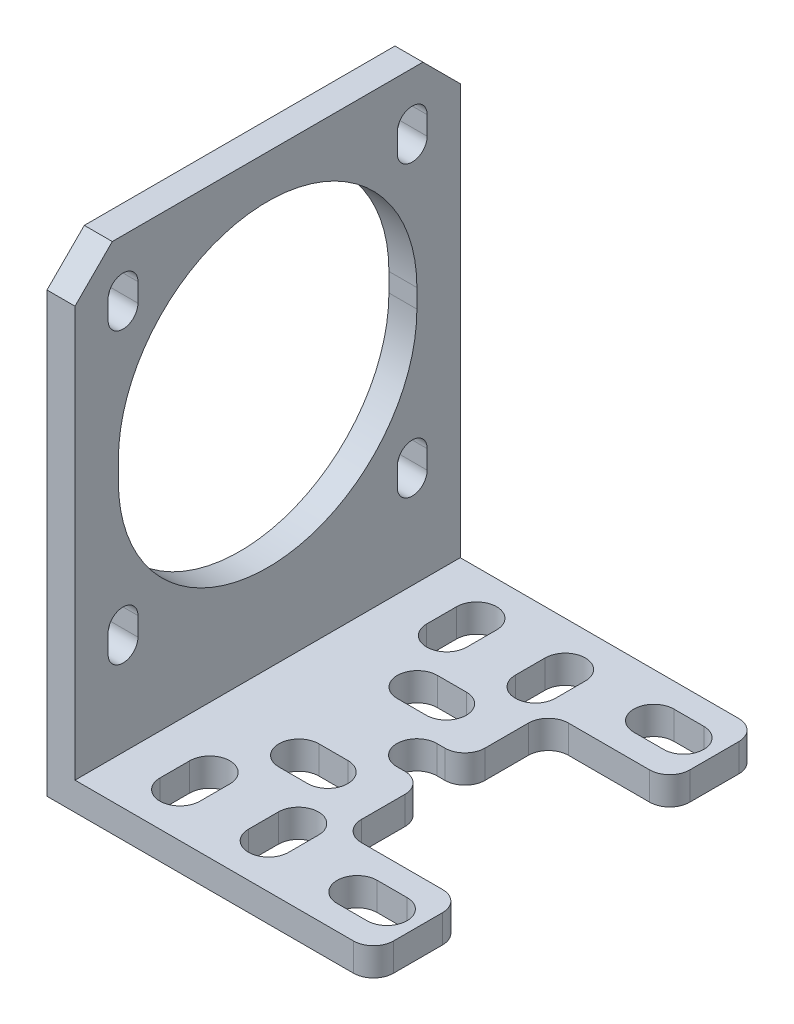
SolidWorks part; units mm, degrees
material "1060 Alloy"
ref_plane "Front Plane" through (0, 0, 0) normal (0, 0, 1) x (1, 0, 0)
ref_plane "Top Plane" through (0, 0, 0) normal (0, 1, 0) x (1, 0, 0)
ref_plane "Right Plane" through (0, 0, 0) normal (1, 0, 0) x (0, 0, -1)
sketch "Sketch1" plane through (0, 0, 0) normal (0, 1, 0) x (1, 0, 0)
  line L0 (-22.0687, 0) -> (25.1163, 0) construction
  line L1 (-17.5, 20.65) -> (15.35, 20.65)
  line L2 (-17.5, 20.65) -> (-17.5, -20.65)
  line L3 (-17.5, -20.65) -> (15.35, -20.65)
  line L4 (17.5, 18.5) -> (17.5, 13.25)
  line L5 (-17.5, 20.65) -> (17.5, -20.65) construction
  line L6 (-17.5, -20.65) -> (17.5, 20.65) construction
  line L7 (-8, 15.9) -> (-8, 12.7) construction
  line L8 (-5.85, 15.9) -> (-5.85, 12.7)
  line L9 (-10.15, 15.9) -> (-10.15, 12.7)
  line L10 (1.5, 15.9) -> (1.5, 12.7) construction
  line L11 (3.65, 15.9) -> (3.65, 12.7)
  line L12 (-0.65, 15.9) -> (-0.65, 12.7)
  line L13 (11, 15.9) -> (14.2, 15.9) construction
  line L14 (11, 18.05) -> (14.2, 18.05)
  line L15 (11, 13.75) -> (14.2, 13.75)
  line L16 (-4.8, 6.35) -> (-1.7, 6.35) construction
  line L17 (-4.8, 8.5) -> (-1.7, 8.5)
  line L18 (-4.8, 4.2) -> (-1.7, 4.2)
  line L19 (6.65, -11.1) -> (15.35, -11.1)
  line L20 (-9.4361, 11.1) -> (-9.4068, 11.1)
  line L21 (4.5, 8.95) -> (4.5, 4.3)
  line L22 (-22.0687, 11.1) -> (25.1163, 11.1) construction
  line L23 (-22.0687, -11.1) -> (25.1163, -11.1) construction
  line L24 (6.65, 11.1) -> (15.35, 11.1)
  line L25 (1.5, 2.15) -> (2.35, 2.15)
  line L26 (1.5, -2.15) -> (2.35, -2.15)
  line L27 (4.5, -4.3) -> (4.5, -8.95)
  line L28 (4.5, 20.65) -> (4.5, -20.65) construction
  line L29 (-4.8, -6.35) -> (-1.7, -6.35) construction
  line L30 (-4.8, -8.5) -> (-1.7, -8.5)
  line L31 (-4.8, -4.2) -> (-1.7, -4.2)
  line L32 (11, -15.9) -> (14.2, -15.9) construction
  line L33 (11, -18.05) -> (14.2, -18.05)
  line L34 (11, -13.75) -> (14.2, -13.75)
  line L35 (1.5, -15.9) -> (1.5, -12.7) construction
  line L36 (3.65, -15.9) -> (3.65, -12.7)
  line L37 (-0.65, -15.9) -> (-0.65, -12.7)
  line L38 (-8, -15.9) -> (-8, -12.7) construction
  line L39 (-5.85, -15.9) -> (-5.85, -12.7)
  line L40 (-10.15, -15.9) -> (-10.15, -12.7)
  line L41 (17.5, -13.25) -> (17.5, -18.5)
  line L42 (17.5, 20.65) -> (17.5, -20.65) construction
  arc A0 (-5.85, 15.9) -> (-10.15, 15.9) centre (-8, 15.9) ccw
  arc A1 (-10.15, 12.7) -> (-5.85, 12.7) centre (-8, 12.7) ccw
  arc A2 (3.65, 15.9) -> (-0.65, 15.9) centre (1.5, 15.9) ccw
  arc A3 (-0.65, 12.7) -> (3.65, 12.7) centre (1.5, 12.7) ccw
  arc A4 (11, 18.05) -> (11, 13.75) centre (11, 15.9) ccw
  arc A5 (14.2, 13.75) -> (14.2, 18.05) centre (14.2, 15.9) ccw
  arc A6 (-4.8, 8.5) -> (-4.8, 4.2) centre (-4.8, 6.35) ccw
  arc A7 (-1.7, 4.2) -> (-1.7, 8.5) centre (-1.7, 6.35) ccw
  arc A8 (1.8038, 2.1284) -> (1.8038, -2.1284) centre (1.5, 0) ccw
  arc A9 (-4.8, -8.5) -> (-4.8, -4.2) centre (-4.8, -6.35) cw
  arc A10 (-1.7, -4.2) -> (-1.7, -8.5) centre (-1.7, -6.35) cw
  arc A11 (11, -18.05) -> (11, -13.75) centre (11, -15.9) cw
  arc A12 (14.2, -13.75) -> (14.2, -18.05) centre (14.2, -15.9) cw
  arc A13 (3.65, -15.9) -> (-0.65, -15.9) centre (1.5, -15.9) cw
  arc A14 (-0.65, -12.7) -> (3.65, -12.7) centre (1.5, -12.7) cw
  arc A15 (-5.85, -15.9) -> (-10.15, -15.9) centre (-8, -15.9) cw
  arc A16 (-10.15, -12.7) -> (-5.85, -12.7) centre (-8, -12.7) cw
  arc A17 (4.5, 8.95) -> (6.65, 11.1) centre (6.65, 8.95) cw
  arc A18 (15.35, 11.1) -> (17.5, 13.25) centre (15.35, 13.25) ccw
  arc A19 (15.35, 20.65) -> (17.5, 18.5) centre (15.35, 18.5) cw
  arc A22 (15.35, -20.65) -> (17.5, -18.5) centre (15.35, -18.5) ccw
  arc A23 (17.5, -13.25) -> (15.35, -11.1) centre (15.35, -13.25) ccw
  arc A24 (6.65, -11.1) -> (4.5, -8.95) centre (6.65, -8.95) cw
  arc A25 (2.35, -2.15) -> (4.5, -4.3) centre (2.35, -4.3) cw
  arc A26 (2.35, 2.15) -> (4.5, 4.3) centre (2.35, 4.3) ccw
  point P0 (0, 0)
  point P10 (-8, 14.3)
  point P17 (1.5, 14.3)
  point P24 (12.6, 15.9)
  point P31 (-3.25, 6.35)
  point P56 (-3.25, -6.35)
  point P63 (12.6, -15.9)
  point P70 (1.5, -14.3)
  point P77 (-8, -14.3)
  point P103 (4.5, -11.1)
  point P106 (4.5, -2.15)
  dimension "D3" = 2.15
  dimension "D7" = 2.15
  dimension "D12" = 2.15
  dimension "D14" = 2.15
  dimension "D17" = 3.2
  dimension "D23" = 3.2
  dimension "D21" = 4.3
  dimension "D22" = 2.15
  dimension "D24" = 2.15
  dimension "D25" = 2.15
  dimension "D1" = 41.3
  dimension "D2" = 35
  dimension "D4" = 15.9
  dimension "D5" = 12.7
  dimension "D6" = 9.5
  dimension "D8" = 9.5
  dimension "D9" = 12.7
  dimension "D10" = 15.9
  dimension "D11" = 9.5
  dimension "D13" = 3.2
  dimension "D15" = 6.35
  dimension "D16" = 3.2
  dimension "D18" = 11.1
  dimension "D19" = 11.1
  dimension "D20" = 13
extrude "Boss-Extrude1" add sketch "Sketch1" along normal blind 3
sketch "Sketch2" plane through (0, 3, 0) normal (0, 1, 0) x (1, 0, 0)
  line L0 (-17.5, 20.65) -> (15.35, 20.65) construction
  line L1 (-17.5, -20.65) -> (-14.5, -20.65)
  line L2 (-17.5, -20.65) -> (-17.5, 20.65)
  line L3 (-17.5, 20.65) -> (-14.5, 20.65)
  line L4 (-14.5, -20.65) -> (-14.5, 20.65)
  dimension "D1" = 3
extrude "Boss-Extrude2" add sketch "Sketch2" along normal blind 48
sketch "Sketch3" plane through (-14.5, 0, 0) normal (1, 0, 0) x (0, 0, -1)
  line L0 (-29.2938, 28.4) -> (35.3405, 28.4) construction
  line L1 (20.65, 0) -> (-20.65, 0) construction
  line L2 (0, 54.8863) -> (0, -4.9814) construction
  line L3 (-15.5, 54.8863) -> (-15.5, -4.9814) construction
  line L4 (15.5, 53.8818) -> (15.5, -5.9859) construction
  line L5 (-29.2938, 30.4) -> (35.3405, 30.4) construction
  line L6 (-16, 30.4) -> (-16, 28.4)
  line L7 (16, 30.4) -> (16, 28.4)
  line L8 (15.5, 45.9) -> (15.5, 43.9) construction
  line L9 (17.1, 45.9) -> (17.1, 43.9)
  line L10 (13.9, 45.9) -> (13.9, 43.9)
  line L11 (-29.2938, 29.4) -> (35.3405, 29.4) construction
  line L12 (-15.5, 45.9) -> (-15.5, 43.9) construction
  line L13 (-17.1, 45.9) -> (-17.1, 43.9)
  line L14 (-13.9, 45.9) -> (-13.9, 43.9)
  line L15 (15.5, 12.9) -> (15.5, 14.9) construction
  line L16 (17.1, 12.9) -> (17.1, 14.9)
  line L17 (13.9, 12.9) -> (13.9, 14.9)
  line L18 (-15.5, 12.9) -> (-15.5, 14.9) construction
  line L19 (-17.1, 12.9) -> (-17.1, 14.9)
  line L20 (-13.9, 12.9) -> (-13.9, 14.9)
  arc A0 (16, 30.4) -> (-16, 30.4) centre (0, 30.4) ccw
  arc A1 (-16, 28.4) -> (16, 28.4) centre (0, 28.4) ccw
  arc A2 (17.1, 45.9) -> (13.9, 45.9) centre (15.5, 45.9) ccw
  arc A3 (13.9, 43.9) -> (17.1, 43.9) centre (15.5, 43.9) ccw
  arc A4 (-17.1, 45.9) -> (-13.9, 45.9) centre (-15.5, 45.9) cw
  arc A5 (-13.9, 43.9) -> (-17.1, 43.9) centre (-15.5, 43.9) cw
  arc A6 (17.1, 12.9) -> (13.9, 12.9) centre (15.5, 12.9) cw
  arc A7 (13.9, 14.9) -> (17.1, 14.9) centre (15.5, 14.9) cw
  arc A8 (-17.1, 12.9) -> (-13.9, 12.9) centre (-15.5, 12.9) ccw
  arc A9 (-13.9, 14.9) -> (-17.1, 14.9) centre (-15.5, 14.9) ccw
  point P21 (15.5, 44.9)
  point P30 (-15.5, 44.9)
  point P37 (15.5, 13.9)
  point P44 (-15.5, 13.9)
  dimension "D2" = 1.6
  dimension "D5" = 32
  dimension "D6" = 32
  dimension "D9" = 1
  dimension "D1" = 28.4
  dimension "D7" = 15.5
  dimension "D3" = 2
  dimension "D4" = 15.5
  dimension "D8" = 15.5
  dimension "D10" = 14.9
extrude "Cut-Extrude1" cut sketch "Sketch3" against normal blind 48
chamfer "Chamfer1" distance 4 angle 45 2 edges at (-16, 51, -20.65) (-16, 51, 20.65)
